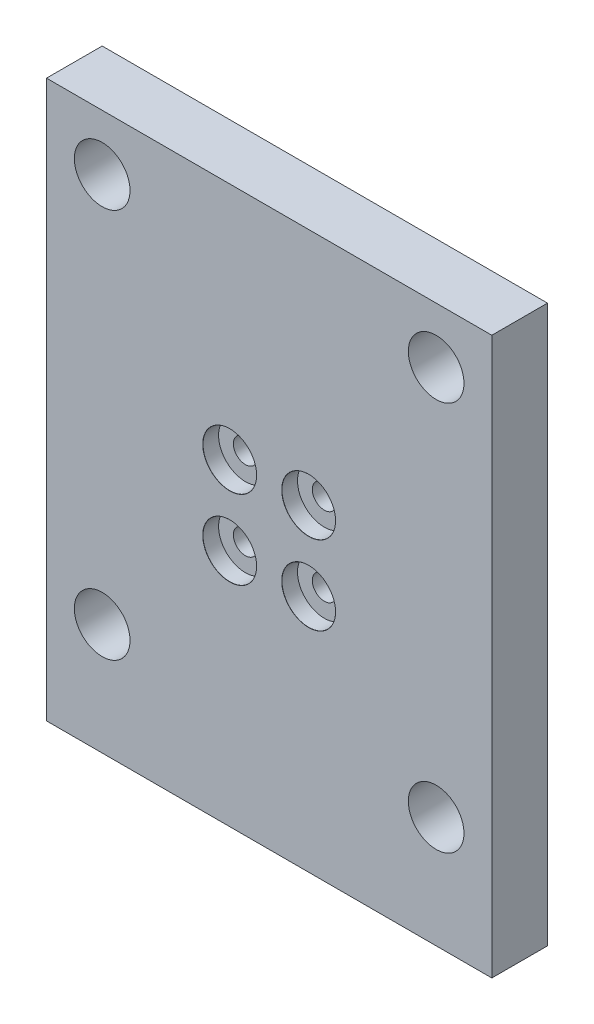
SolidWorks part; units mm, degrees
material "6061 Alloy"
ref_plane "Front" through (0, 0, 0) normal (0, 0, 1) x (1, 0, 0)
ref_plane "Top" through (0, 0, 0) normal (0, 1, 0) x (1, 0, 0)
ref_plane "Right" through (0, 0, 0) normal (1, 0, 0) x (0, 0, -1)
sketch "Sketch1" plane through (0, 0, 0) normal (0, 0, 1) x (1, 0, 0)
  line L1 (0, 0) -> (101.6, 0)
  line L2 (0, 0) -> (0, 127)
  line L3 (0, 127) -> (101.6, 127)
  line L4 (101.6, 0) -> (101.6, 127)
  dimension "D1" = 101.6
  dimension "D2" = 127
extrude "Boss-Extrude1" add sketch "Sketch1" along normal blind 12.7
sketch "Sketch4" plane through (0, 0, 12.7) normal (0, 0, 1) x (1, 0, 0)
  line L0 (0, 127) -> (0, 0) construction
  line L2 (50.8, 105.5447) -> (50.8, -4.7693) construction
  line L3 (0, 0) -> (101.6, 0) construction
  circle A0 centre (12.7, 114.3) radius 6.35
  circle A1 centre (12.7, 25.4) radius 6.35
  circle A2 centre (88.9, 25.4) radius 6.35
  circle A3 centre (88.9, 114.3) radius 6.35
  dimension "D1" = 12.7
  dimension "D2" = 12.7
  dimension "D3" = 12.7
  dimension "D4" = 25.4
  dimension "D6" = 88.9
extrude "Cut-Extrude9" cut sketch "Sketch4" against normal through all
sketch "Sketch5" plane through (0, 0, 12.7) normal (0, 0, 1) x (1, 0, 0)
  line L0 (50.8, 0) -> (50.8, 127) construction
  line L1 (0, 0) -> (101.6, 0) construction
  line L2 (101.6, 127) -> (0, 127) construction
  line L3 (-5.6233, 63.5) -> (108.9481, 63.5) construction
  line L4 (41.7957, 72.5) -> (59.8043, 54.5) construction
  line L5 (59.8043, 72.5) -> (41.7957, 54.5) construction
  circle A0 centre (41.7957, 54.5) radius 3.5299
  circle A1 centre (41.7957, 72.5) radius 3.2524
  circle A2 centre (59.8043, 72.5) radius 3.5727
  circle A3 centre (59.8043, 54.5) radius 3.3171
  point P18 (50.8, 63.5)
  point P19 (50.8, 63.5)
  dimension "D1" = 18
  dimension "D2" = 18.0086
  dimension "D3" = 63.5
hole_wizard "CBORE for M5 Hex Head Bolt1" positions "Sketch7" profile "Sketch8" counterbore size "M5" standard "ANSI Metric" end condition up to next
sketch "Sketch7" plane through (0, 0, 12.7) normal (0, 0, 1) x (1, 0, 0)
  point P0 (41.7957, 72.5)
  point P3 (59.8043, 72.5)
  point P6 (59.8043, 54.5)
  point P9 (41.7957, 54.5)
sketch "Sketch8" plane through (41.7957, 72.5, 12.7) normal (1, 0, 0) x (0, -1, 0)
  line L0 (0, 0) -> (0, 12.7)
  line L1 (0, 12.7) -> (2.75, 12.7)
  line L3 (2.75, 12.7) -> (2.75, 3.58)
  line L4 (6.12, 3.58) -> (2.75, 3.58)
  line L5 (6.12, 3.58) -> (6.12, 0.025)
  line L6 (6.12, 0.025) -> (6.145, 0)
  line L7 (6.145, 0) -> (0, 0)
  line L8 (-6.12, 0.025) -> (-6.145, 0) construction
  line L11 (0, -6.35) -> (0, 107.95) construction
  dimension "Thru Hole Dia." = 5.5
  dimension "Thru Hole Depth" = 12.7
  dimension "C'Bore Dia." = 12.24
  dimension "C'Bore Depth" = 3.58
  dimension "Near C'Sink Dia." = 12.29
  dimension "Near C'Sink Angle" = 90
